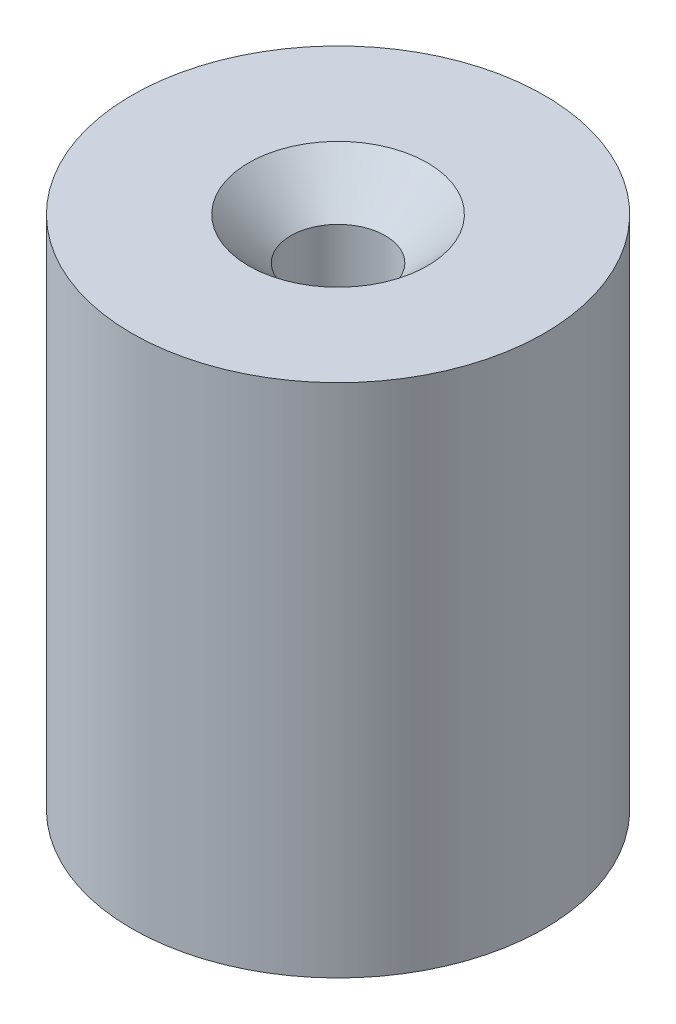
SolidWorks part; units mm, degrees
ref_plane "Front Plane" through (0, 0, 0) normal (0, 0, 1) x (1, 0, 0)
ref_plane "Top Plane" through (0, 0, 0) normal (0, 1, 0) x (1, 0, 0)
ref_plane "Right Plane" through (0, 0, 0) normal (1, 0, 0) x (0, 0, -1)
sketch "Sketch1" plane through (0, 0, 0) normal (0, 1, 0) x (1, 0, 0)
  circle A0 centre (0, 0) radius 12
extrude "Boss-Extrude1" add sketch "Sketch1" along normal blind 30
hole_wizard "CSK for M5 Countersunk Flat Head Screw1" positions "Sketch2" profile "Sketch4" countersink size "M5" standard "ISO"
sketch "Sketch2" plane through (0, 30, 0) normal (0, 1, 0) x (1, 0, 0)
  point P0 (0, 0)
sketch "Sketch4" plane through (0, 30, 0) normal (1, 0, 0) x (0, 0, 1)
  line L0 (0, 0) -> (0, 13.6524)
  line L1 (0, 13.6524) -> (2.75, 12)
  line L2 (2.75, 12) -> (2.75, 2.45)
  line L3 (2.75, 2.45) -> (5.2, 0)
  line L5 (5.2, 0) -> (0, 0)
  line L6 (-2.75, 2.45) -> (-5.2, 0) construction
  line L10 (0, 13.6524) -> (-2.75, 12) construction
  line L11 (0, -6.35) -> (0, 107.95) construction
  dimension "Hole Dia." = 5.5
  dimension "Hole Depth" = 12
  dimension "Near C'Sink Dia." = 10.4
  dimension "Near C'Sink Angle" = 90
  dimension "Drill Angle" = 118
hole_wizard "Ø8.0mm Dowel Hole1" positions "Sketch5" profile "Sketch6" hole size "Ø8.0" standard "ISO"
sketch "Sketch5" plane through (0, 0, 0) normal (0, -1, 0) x (-1, 0, 0)
  point P0 (0, 0)
sketch "Sketch6" plane through (0, 0, 0) normal (1, 0, 0) x (0, 0, -1)
  line L0 (0, 0) -> (0, 14.4034)
  line L1 (0, 14.4034) -> (4, 12)
  line L2 (4, 12) -> (4, 0)
  line L5 (4, 0) -> (0, 0)
  line L10 (0, 14.4034) -> (-4, 12) construction
  line L11 (0, -6.35) -> (0, 107.95) construction
  dimension "Hole Dia." = 8
  dimension "Hole Depth" = 12
  dimension "Drill Angle" = 118
